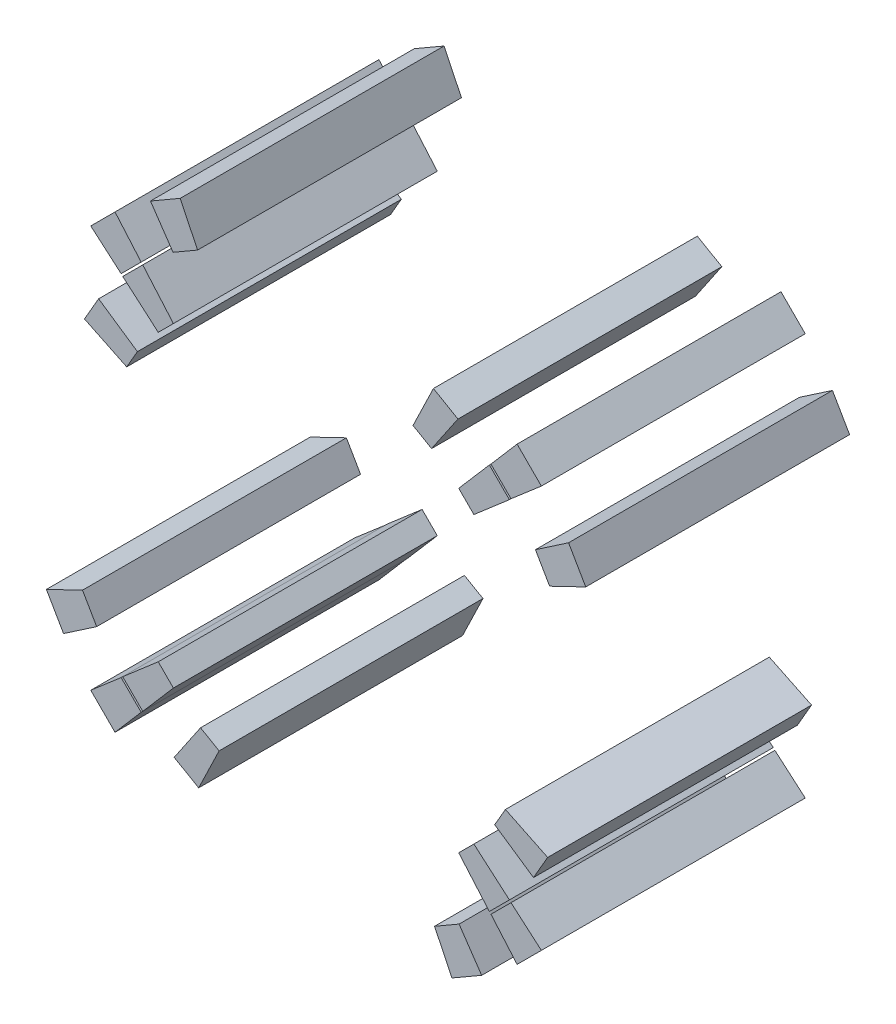
SolidWorks part; units mm, degrees
ref_plane "Спереди" through (0, 0, 0) normal (0, 0, 1) x (1, 0, 0)
ref_plane "Сверху" through (0, 0, 0) normal (0, 1, 0) x (1, 0, 0)
ref_plane "Справа" through (0, 0, 0) normal (1, 0, 0) x (0, 0, -1)
sketch "Эскиз1" plane through (0, 0, 0) normal (0, 0, 1) x (1, 0, 0)
  line L0 (35.4045, 17.9613) -> (40.8774, 20.5983)
  line L1 (40.8774, 20.5983) -> (38.2774, 25.1017)
  line L2 (38.2774, 25.1017) -> (33.2572, 21.6806)
  line L3 (33.2572, 21.6806) -> (35.4045, 17.9613)
  line L4 (23.9243, 21.6262) -> (29.3077, 26.2709)
  line L5 (29.3077, 26.2709) -> (26.2709, 29.3077)
  line L6 (26.2709, 29.3077) -> (21.6262, 23.9243)
  line L7 (21.6262, 23.9243) -> (23.9243, 21.6262)
  line L8 (29.5494, 26.5127) -> (34.1533, 30.4763)
  line L9 (34.1533, 30.4763) -> (30.4763, 34.1533)
  line L10 (30.4763, 34.1533) -> (26.5127, 29.5494)
  line L11 (26.5127, 29.5494) -> (29.5494, 26.5127)
  line L12 (17.5118, 27.0813) -> (21.5096, 32.9611)
  line L13 (21.5096, 32.9611) -> (17.7904, 35.1085)
  line L14 (17.7904, 35.1085) -> (14.6972, 28.7063)
  line L15 (14.6972, 28.7063) -> (17.5118, 27.0813)
  line L16 (-17.9613, 35.4045) -> (-20.5983, 40.8774)
  line L17 (-20.5983, 40.8774) -> (-25.1017, 38.2774)
  line L18 (-25.1017, 38.2774) -> (-21.6806, 33.2572)
  line L19 (-21.6806, 33.2572) -> (-17.9613, 35.4045)
  line L20 (-21.6262, 23.9243) -> (-26.2709, 29.3077)
  line L21 (-26.2709, 29.3077) -> (-29.3077, 26.2709)
  line L22 (-29.3077, 26.2709) -> (-23.9243, 21.6262)
  line L23 (-23.9243, 21.6262) -> (-21.6262, 23.9243)
  line L24 (-26.5127, 29.5494) -> (-30.4763, 34.1533)
  line L25 (-30.4763, 34.1533) -> (-34.1533, 30.4763)
  line L26 (-34.1533, 30.4763) -> (-29.5494, 26.5127)
  line L27 (-29.5494, 26.5127) -> (-26.5127, 29.5494)
  line L28 (-27.0813, 17.5118) -> (-32.9611, 21.5096)
  line L29 (-32.9611, 21.5096) -> (-35.1085, 17.7904)
  line L30 (-35.1085, 17.7904) -> (-28.7063, 14.6972)
  line L31 (-28.7063, 14.6972) -> (-27.0813, 17.5118)
  line L32 (-35.4045, -17.9613) -> (-40.8774, -20.5983)
  line L33 (-40.8774, -20.5983) -> (-38.2774, -25.1017)
  line L34 (-38.2774, -25.1017) -> (-33.2572, -21.6806)
  line L35 (-33.2572, -21.6806) -> (-35.4045, -17.9613)
  line L36 (-23.9243, -21.6262) -> (-29.3077, -26.2709)
  line L37 (-29.3077, -26.2709) -> (-26.2709, -29.3077)
  line L38 (-26.2709, -29.3077) -> (-21.6262, -23.9243)
  line L39 (-21.6262, -23.9243) -> (-23.9243, -21.6262)
  line L40 (-29.5494, -26.5127) -> (-34.1533, -30.4763)
  line L41 (-34.1533, -30.4763) -> (-30.4763, -34.1533)
  line L42 (-30.4763, -34.1533) -> (-26.5127, -29.5494)
  line L43 (-26.5127, -29.5494) -> (-29.5494, -26.5127)
  line L44 (-17.5118, -27.0813) -> (-21.5096, -32.9611)
  line L45 (-21.5096, -32.9611) -> (-17.7904, -35.1085)
  line L46 (-17.7904, -35.1085) -> (-14.6972, -28.7063)
  line L47 (-14.6972, -28.7063) -> (-17.5118, -27.0813)
  line L48 (17.9613, -35.4045) -> (20.5983, -40.8774)
  line L49 (20.5983, -40.8774) -> (25.1017, -38.2774)
  line L50 (25.1017, -38.2774) -> (21.6806, -33.2572)
  line L51 (21.6806, -33.2572) -> (17.9613, -35.4045)
  line L52 (21.6262, -23.9243) -> (26.2709, -29.3077)
  line L53 (26.2709, -29.3077) -> (29.3077, -26.2709)
  line L54 (29.3077, -26.2709) -> (23.9243, -21.6262)
  line L55 (23.9243, -21.6262) -> (21.6262, -23.9243)
  line L56 (26.5127, -29.5494) -> (30.4763, -34.1533)
  line L57 (30.4763, -34.1533) -> (34.1533, -30.4763)
  line L58 (34.1533, -30.4763) -> (29.5494, -26.5127)
  line L59 (29.5494, -26.5127) -> (26.5127, -29.5494)
  line L60 (27.0813, -17.5118) -> (32.9611, -21.5096)
  line L61 (32.9611, -21.5096) -> (35.1085, -17.7904)
  line L62 (35.1085, -17.7904) -> (28.7063, -14.6972)
  line L63 (28.7063, -14.6972) -> (27.0813, -17.5118)
extrude "Coil_sides" add sketch "Эскиз1" along normal blind 40 from offset 20 separate body
